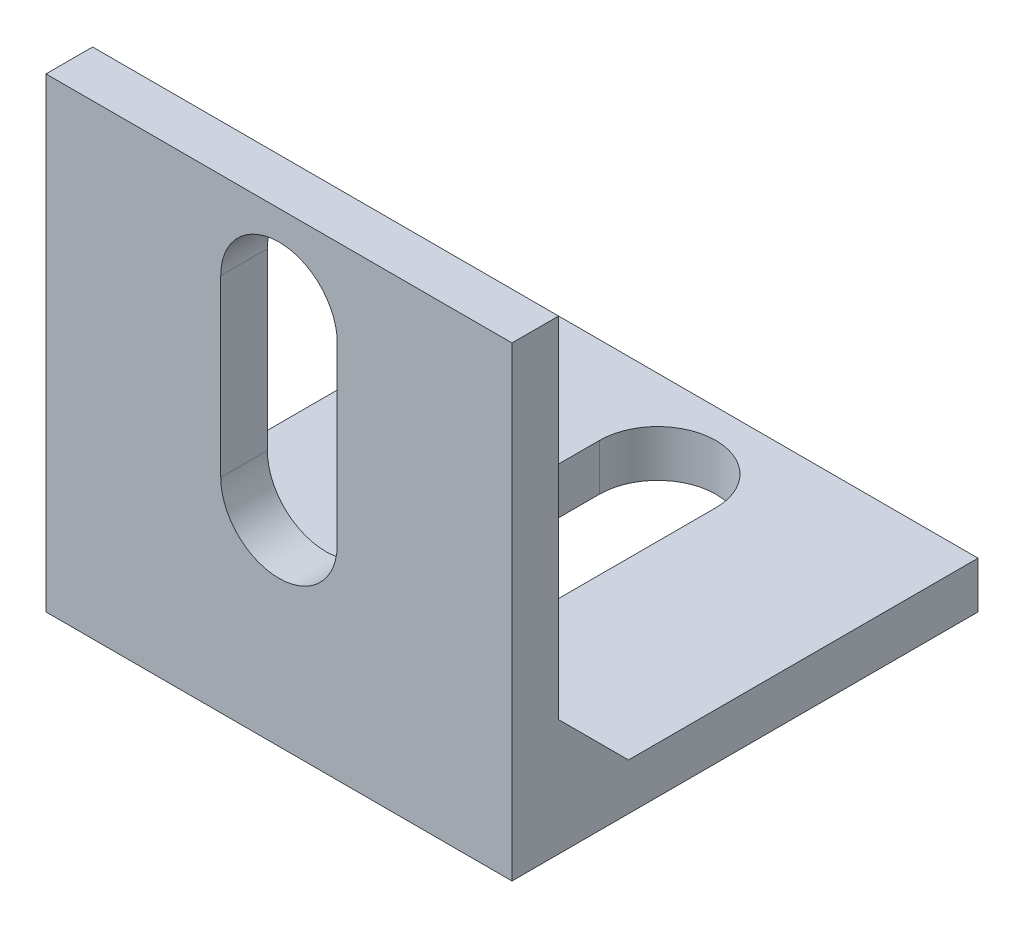
SolidWorks part; units mm, degrees
ref_plane "Front Plane" through (0, 0, 0) normal (0, 0, 1) x (1, 0, 0)
ref_plane "Top Plane" through (0, 0, 0) normal (0, 1, 0) x (1, 0, 0)
ref_plane "Right Plane" through (0, 0, 0) normal (1, 0, 0) x (0, 0, -1)
sketch "Sketch1" plane through (0, 0, 0) normal (1, 0, 0) x (0, 0, -1)
  line L0 (20, 0) -> (0, 0)
  line L1 (0, 0) -> (0, 20)
  line L2 (0, 20) -> (2, 20)
  line L3 (2, 20) -> (2, 5)
  line L4 (2, 5) -> (5, 2)
  line L5 (5, 2) -> (20, 2)
  line L6 (20, 2) -> (20, 0)
  point P3 (2, 5.9049)
  dimension "D1" = 2
  dimension "D2" = 20
  dimension "D3" = 15
extrude "Body" add sketch "Sketch1" along normal mid plane 20
sketch "Sketch3" plane through (0, 0, -2) normal (0, 0, -1) x (-1, 0, 0)
  line L0 (0, 8.75) -> (0, 16.25) construction
  line L1 (-2.5, 8.75) -> (-2.5, 16.25)
  line L2 (2.5, 8.75) -> (2.5, 16.25)
  arc A0 (-2.5, 8.75) -> (2.5, 8.75) centre (0, 8.75) ccw
  arc A1 (2.5, 16.25) -> (-2.5, 16.25) centre (0, 16.25) ccw
  point P3 (0, 12.5)
  dimension "D1" = 7.5
  dimension "D2" = 5
  dimension "D3" = 12.5
extrude "Fixation_Hole" cut sketch "Sketch3" against normal through all
ref_plane "Plane1" through (0, 0, 0) normal (0, -0.7071, -0.7071) x (-1, 0, 0)
mirror "Mirror1" about plane through (0, 0, 0) normal (0, -0.7071, -0.7071) of "Fixation_Hole"
